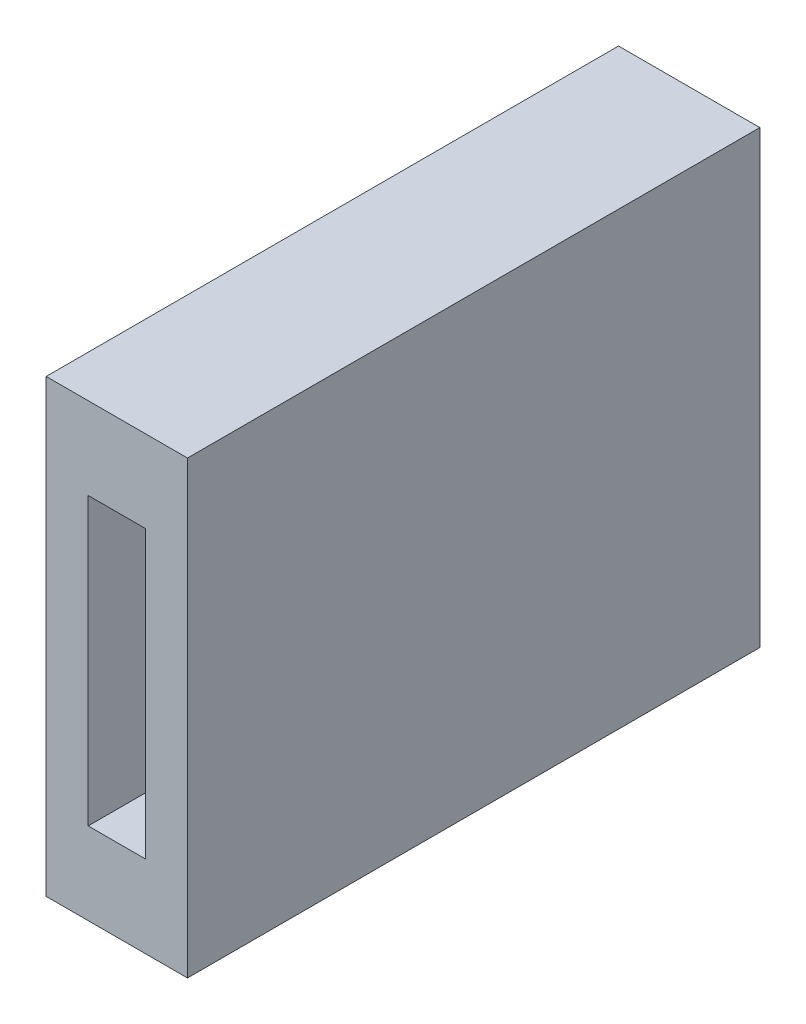
SolidWorks part; units mm, degrees
ref_plane "前视基准面" through (0, 0, 0) normal (0, 0, 1) x (1, 0, 0)
ref_plane "上视基准面" through (0, 0, 0) normal (0, 1, 0) x (1, 0, 0)
ref_plane "右视基准面" through (0, 0, 0) normal (1, 0, 0) x (0, 0, -1)
sketch "草图1" plane through (0, 0, 0) normal (0, 0, 1) x (1, 0, 0)
  line L1 (-2.5, -12.5) -> (2.5, -12.5)
  line L2 (-2.5, -12.5) -> (-2.5, 12.5)
  line L3 (-2.5, 12.5) -> (2.5, 12.5)
  line L4 (2.5, -12.5) -> (2.5, 12.5)
  line L5 (-2.5, -12.5) -> (2.5, 12.5) construction
  line L6 (-2.5, 12.5) -> (2.5, -12.5) construction
  line L7 (-6.1721, -19.6696) -> (6.1721, -19.6696)
  line L8 (-6.1721, -19.6696) -> (-6.1721, 19.6696)
  line L9 (-6.1721, 19.6696) -> (6.1721, 19.6696)
  line L10 (6.1721, -19.6696) -> (6.1721, 19.6696)
  line L11 (-6.1721, -19.6696) -> (6.1721, 19.6696) construction
  line L12 (-6.1721, 19.6696) -> (6.1721, -19.6696) construction
  point P0 (0, 0)
  point P6 (0, 0)
  dimension "D1" = 25
  dimension "D2" = 5
extrude "凸台-拉伸1" add sketch "草图1" along normal blind 50
